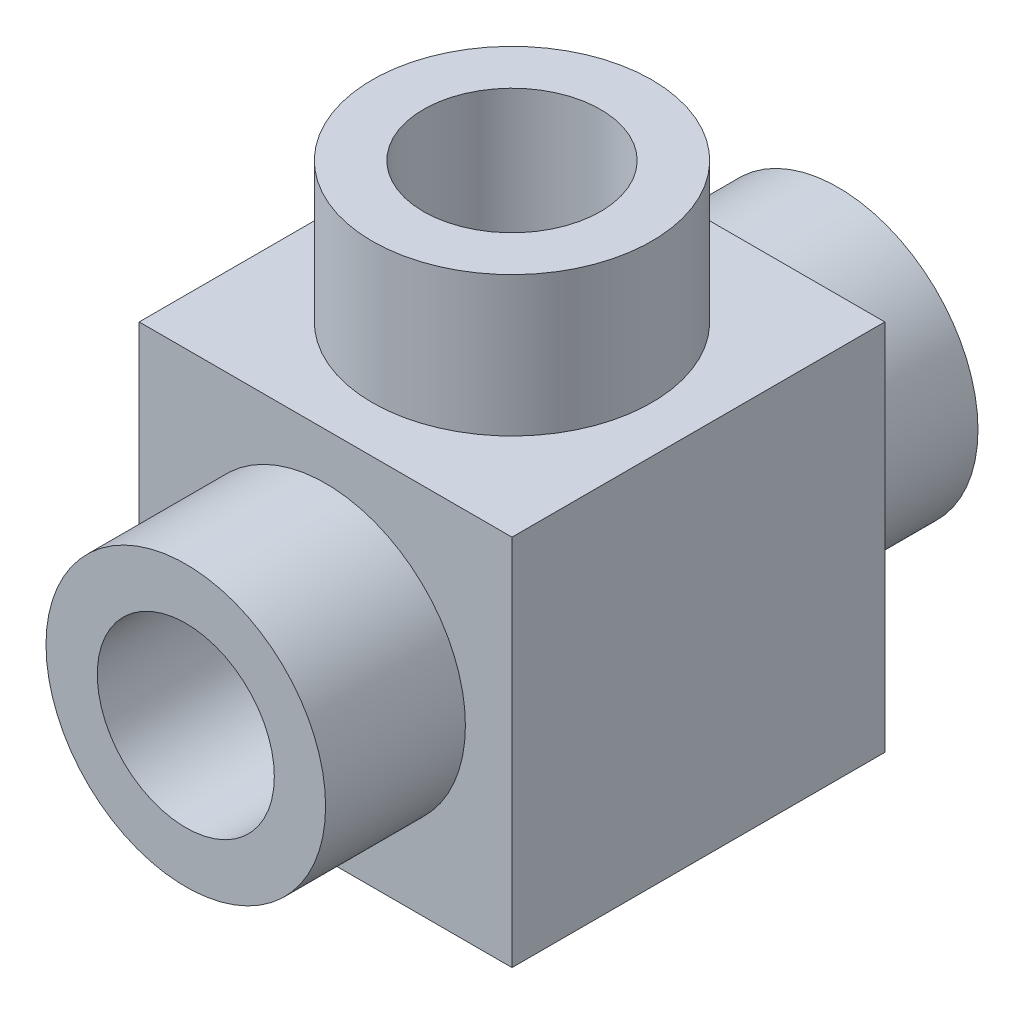
SolidWorks part; units mm, degrees
ref_plane "Alzado" through (0, 0, 0) normal (0, 0, 1) x (1, 0, 0)
ref_plane "Planta" through (0, 0, 0) normal (0, 1, 0) x (1, 0, 0)
ref_plane "Vista lateral" through (0, 0, 0) normal (1, 0, 0) x (0, 0, -1)
sketch "Croquis1" plane through (0, 0, 0) normal (0, 0, 1) x (1, 0, 0)
  circle A1 centre (0, 0) radius 19
  circle A2 centre (0, 0) radius 30
extrude "Saliente-Extruir1" add sketch "Croquis1" along normal blind 30
sketch "Croquis2" plane through (0, 0, 0) normal (0, 0, 1) x (1, 0, 0)
  line L1 (40, 40) -> (-40, 40)
  line L2 (40, 40) -> (40, -40)
  line L3 (40, -40) -> (-40, -40)
  line L4 (-40, 40) -> (-40, -40)
  point P0 (0, 0)
extrude "Saliente-Extruir2" add sketch "Croquis2" against normal blind 80
ref_plane "Plano1" through (40, 0, 0) normal (1, 0, 0) x (0, 0, -1)
ref_plane "Plano2" through (0, 40, 0) normal (0, 1, 0) x (1, 0, 0)
sketch "Croquis4" plane through (0, 40, 0) normal (0, 1, 0) x (1, 0, 0)
  circle A0 centre (0, 40) radius 19
  circle A1 centre (0, 40) radius 30
extrude "Saliente-Extruir4" add sketch "Croquis4" along normal blind 30
ref_plane "Plano4" through (0, 0, -80) normal (0, 0, 1) x (1, 0, 0)
sketch "Croquis6" plane through (0, 0, -80) normal (0, 0, 1) x (1, 0, 0)
  circle A0 centre (0, 0) radius 19
  circle A1 centre (0, 0) radius 30
extrude "Saliente-Extruir6" add sketch "Croquis6" against normal blind 30
